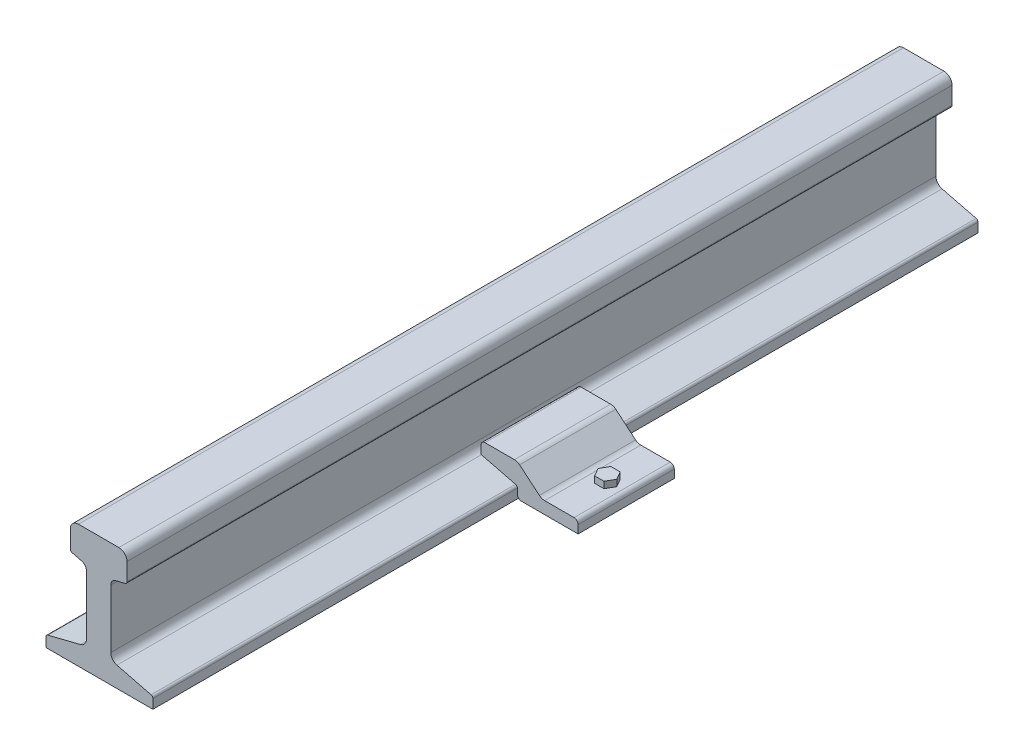
SolidWorks part; units mm, degrees
ref_plane "前视基准面" through (0, 0, 0) normal (0, 0, 1) x (1, 0, 0)
ref_plane "上视基准面" through (0, 0, 0) normal (0, 1, 0) x (1, 0, 0)
ref_plane "右视基准面" through (0, 0, 0) normal (1, 0, 0) x (0, 0, -1)
sketch "草图1" plane through (0, 0, 0) normal (0, 0, 1) x (1, 0, 0)
  line L0 (0, -1000) -> (0, 49000) construction
  line L1 (-35, -1000.4455) -> (-35, 48999.5545) construction
  line L2 (35, -1000.1485) -> (35, 48999.8515) construction
  line L3 (-65, -895.965) -> (-65, 49104.035) construction
  line L4 (67, -918.509) -> (67, 49081.491) construction
  line L5 (-15, -968.6067) -> (-15, 49031.3933) construction
  line L6 (15, -969.4417) -> (15, 49030.5583) construction
  line L7 (-1051.2415, 49.6) -> (48948.7585, 49.6) construction
  line L8 (-1057, -54.6) -> (48943, -54.6) construction
  line L9 (-35, 49.6) -> (-35, 83.5)
  line L10 (-1000, 0) -> (49000, 0) construction
  line L11 (-35, 83.5) -> (35, 83.5)
  line L12 (35, 83.5) -> (35, 49.6)
  line L13 (-35, 49.6) -> (365, -50.4) construction
  line L14 (35, 49.6) -> (-365, -50.4) construction
  line L15 (-35, 49.6) -> (-15, 44.6)
  line L16 (35, 49.6) -> (15, 44.6)
  line L17 (-65, -68.5) -> (67, -68.5)
  line L18 (-15, 44.6) -> (-15, -42.1)
  line L19 (15, 44.6) -> (15, -41.6)
  line L20 (-65, -54.6) -> (-15, -42.1)
  line L21 (67, -54.6) -> (67, -68.5)
  line L22 (15, -41.6) -> (67, -54.6)
  line L23 (-65, -54.6) -> (-65, -68.5)
  dimension "D1" = 35
  dimension "D2" = 35
  dimension "D3" = 65
  dimension "D4" = 67
  dimension "D5" = 15
  dimension "D6" = 15
  dimension "D7" = 49.6
  dimension "D9" = 83.5
  dimension "D10" = 100
  dimension "D11" = 400
  dimension "D12" = 100
  dimension "D13" = 400
  dimension "D14" = 152
  dimension "D16" = 54.6
extrude "拉伸1" add sketch "草图1" along normal blind 1018.75
fillet "圆角1" radius 10 2 edges at (-15, -42.1, 509.375) (15, -41.6, 509.375)
fillet "圆角2" radius 8 2 edges at (-15, 44.6, 509.375) (15, 44.6, 509.375)
fillet "圆角3" radius 3 2 edges at (35, 49.6, 509.375) (-35, 49.6, 509.375)
fillet "圆角4" radius 10 2 edges at (-35, 83.5, 509.375) (35, 83.5, 509.375)
fillet "圆角5" radius 3 2 edges at (-65, -54.6, 509.375) (67, -54.6, 509.375)
ref_plane "基准面3" through (0, 0, 450) normal (0, 0, 1) x (1, 0, 0)
sketch "草图4" plane through (0, 0, 450) normal (0, 0, 1) x (1, 0, 0)
  line L0 (142, -68.5) -> (142, -58.5)
  line L2 (137, -53.5) -> (100.6372, -53.5)
  line L3 (94.2127, -51.1633) -> (69.7873, -30.6867)
  line L4 (63.3628, -28.35) -> (27, -28.35)
  line L5 (22, -33.35) -> (22, -43.35)
  line L6 (64.7276, -54.0319) -> (22.5746, -43.4937) construction
  line L7 (22, -43.35) -> (64.7276, -54.0319)
  line L8 (142, -68.5) -> (72, -68.5)
  line L9 (67, -63.5) -> (67, -56.9423)
  line L11 (67, -68.5) -> (67, -56.9423) construction
  line L12 (-65, -68.5) -> (67, -68.5) construction
  arc A0 (64.7276, -54.0319) -> (67, -56.9423) centre (64, -56.9423) cw
  arc A1 (67, -56.9423) -> (64.7276, -54.0319) centre (64, -56.9423) ccw construction
  arc A2 (137, -53.5) -> (142, -58.5) centre (137, -58.5) cw
  arc A3 (94.2127, -51.1633) -> (100.6372, -53.5) centre (100.6372, -43.5) ccw
  arc A4 (63.3628, -28.35) -> (69.7873, -30.6867) centre (63.3628, -38.35) cw
  arc A5 (22, -33.35) -> (27, -28.35) centre (27, -33.35) cw
  arc A6 (72, -68.5) -> (67, -63.5) centre (72, -63.5) cw
  point P22 (142, -53.5)
  point P25 (97, -53.5)
  point P28 (67, -28.35)
  point P31 (22, -28.35)
  dimension "D7" = 5
  dimension "D8" = 10
  dimension "D9" = 10
  dimension "D10" = 5
  dimension "D11" = 5
  dimension "D1" = 15
  dimension "D2" = 75
  dimension "D3" = 15
  dimension "D4" = 45
  dimension "D5" = 45
  dimension "D6" = 45
extrude "凸台-拉伸1" add sketch "草图4" along normal blind 118.75
sketch "草图5" plane through (0, -53.5, 0) normal (0, 1, 0) x (1, 0, 0)
  line L0 (-863, -509.375) -> (49137, -509.375) construction
  line L1 (137, -568.75) -> (137, -450) construction
  line L2 (118.8186, -1450) -> (118.8186, 48550) construction
  line L3 (137, -450) -> (100.6372, -450) construction
  line L5 (124.5921, -519.375) -> (130.3656, -509.375)
  line L6 (130.3656, -509.375) -> (124.5921, -499.375)
  line L7 (124.5921, -499.375) -> (113.0451, -499.375)
  line L8 (113.0451, -499.375) -> (107.2716, -509.375)
  line L9 (107.2716, -509.375) -> (113.0451, -519.375)
  line L10 (113.0451, -519.375) -> (124.5921, -519.375)
  circle A0 centre (118.8186, -509.375) radius 10 construction
  point P5 (137, -509.375)
  point P10 (118.8186, -450)
  dimension "D1" = 20
extrude "凸台-拉伸2" add sketch "草图5" along normal blind 8
ref_plane "基准面4" through (1, 0, 0) normal (1, 0, 0) x (0, 0, -1)
mirror "镜向1" about plane through (1, 0, 0) normal (1, 0, 0) of "凸台-拉伸2", "凸台-拉伸1"
